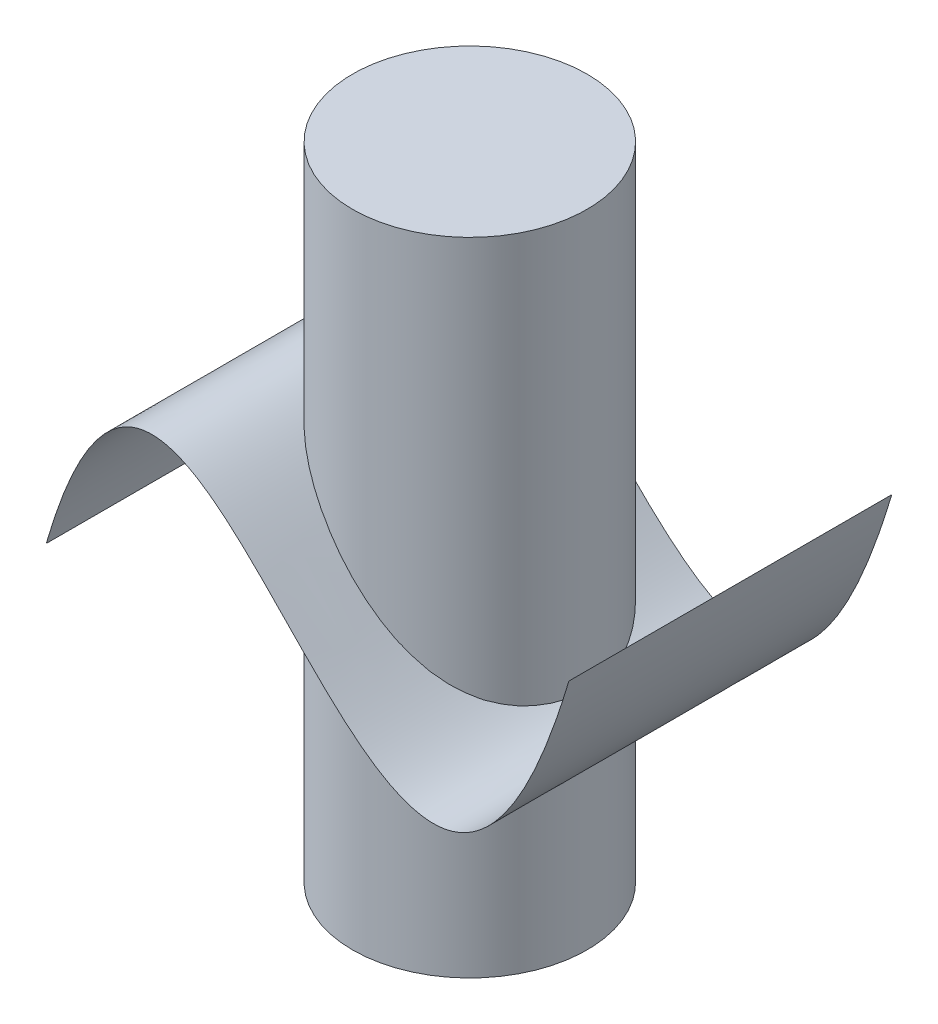
SolidWorks part; units mm, degrees
ref_plane "前视基准面" through (0, 0, 0) normal (0, 0, 1) x (1, 0, 0)
ref_plane "上视基准面" through (0, 0, 0) normal (0, 1, 0) x (1, 0, 0)
ref_plane "右视基准面" through (0, 0, 0) normal (1, 0, 0) x (0, 0, -1)
other "Configuration Table"
sketch "草图1" plane through (0, 0, 0) normal (0, 0, 1) x (1, 0, 0)
  spline S0 degree 3 poles (-85.8726, -24.0496) (-22.8274, 193.3741) (74.8967, -213.2331) (150.4405, 40.2569) knots 0 0 0 0 1 1 1 1
surface "曲面-拉伸1" sketch "草图1" parameters "D1"=146
sketch "草图2" plane through (0, 0, 0) normal (0, 1, 0) x (1, 0, 0)
  circle A0 centre (21.5976, 11.0548) radius 53.0044
  point P2 (21.1063, 28.4968)
  point P3 (21.5976, 11.0548)
extrude "凸台-拉伸1" add sketch "草图2" along normal mid plane 290
sketch3d "3D草图1"
  spline S0 degree 3 poles (21.2444, 1.1157, -64.0592) (24.4232, -2.1595, -64.0592) (27.2203, -5.0469, -63.8359) (32.8022, -10.7278, -62.9385) (35.5868, -13.5217, -62.2648) (39.7817, -17.6026, -60.8643) (41.1829, -18.9445, -60.3319) (43.2923, -20.9235, -59.4221) (43.9967, -21.5776, -59.1003) (45.4084, -22.8733, -58.4165) (46.1141, -23.5134, -58.0553) (49.6189, -26.6515, -56.1596) (52.3702, -28.9826, -54.3496) (55.7189, -31.6232, -51.6252) (56.384, -32.1376, -51.0569) (57.7034, -33.1377, -49.8701) (58.3577, -33.6233, -49.2514) (60.2754, -35.016, -47.3419) (61.5027, -35.8662, -45.9902) (63.8424, -37.4146, -43.1215) (64.9549, -38.1127, -41.6045) (66.524, -39.0507, -39.1974) (67.0304, -39.3452, -38.3731) (68.0071, -39.8989, -36.6788) (68.4789, -40.1588, -35.8054) (69.8161, -40.8772, -33.1539) (70.6083, -41.2774, -31.3373) (71.9898, -41.9474, -27.6093) (72.5791, -42.2173, -25.698) (73.3033, -42.5391, -22.7599) (73.5183, -42.6327, -21.7668) (73.8915, -42.7928, -19.7643) (74.0485, -42.859, -18.7616) (74.4325, -43.0195, -15.7495) (74.5727, -43.0762, -13.7358) (74.6231, -43.0968, -9.6977) (74.5334, -43.0607, -7.6732) (74.2209, -42.9311, -4.6279) (74.0874, -42.8755, -3.6174) (73.7652, -42.7389, -1.6188) (73.5762, -42.6579, -0.6286) (72.9276, -42.3742, 2.3146) (72.3865, -42.1312, 4.2407) (71.4152, -41.6698, 7.0745) (71.0649, -41.4998, 8.0099) (70.3108, -41.1238, 9.8617) (69.9055, -40.9168, 10.7812) (67.775, -39.7977, 15.2683) (65.7316, -38.6277, 18.5404) (62.8356, -36.7512, 22.2586) (62.2378, -36.3543, 22.9851) (61.0149, -35.5218, 24.394) (60.3932, -35.0885, 25.0727) (58.5007, -33.7385, 27.0364) (57.2027, -32.7716, 28.2489) (54.5469, -30.7104, 30.5005) (53.1891, -29.6161, 31.5396) (50.4217, -27.3072, 33.459) (49.0329, -26.11, 34.325) (44.8579, -22.4107, 36.6803) (42.0622, -19.8002, 37.9306) (37.8426, -15.7226, 39.4209) (36.4315, -14.3362, 39.8527) (33.5971, -11.5166, 40.5943) (32.1853, -10.095, 40.901) (27.9697, -5.8163, 41.6425) (25.18, -2.94, 41.9021) (19.5961, 2.8146, 41.9854) (16.8022, 5.6932, 41.8091) (12.5721, 9.9776, 41.195) (11.1542, 11.4013, 40.9312) (8.3031, 14.2255, 40.2761) (6.8812, 15.615, 39.8875) (2.6197, 19.7021, 38.5255) (-0.2161, 22.3198, 37.3596) (-3.7705, 25.4021, 35.4917) (-4.4818, 26.009, 35.0973) (-5.9056, 27.2019, 34.2633) (-6.6175, 27.7873, 33.8238) (-8.7325, 29.4919, 32.4467) (-10.1221, 30.5651, 31.4468) (-12.8536, 32.5745, 29.2644) (-14.1954, 33.5105, 28.0822) (-16.1629, 34.8043, 26.1535) (-16.8127, 35.2181, 25.483) (-18.0876, 36.0035, 24.094) (-18.7087, 36.3727, 23.3803) (-21.7284, 38.1056, 19.7147) (-23.8739, 39.1283, 16.4734) (-26.1334, 40.0572, 12.015) (-26.5651, 40.226, 11.1001) (-27.3717, 40.5281, 9.2551) (-27.748, 40.662, 8.3227) (-28.7965, 41.02, 5.4963) (-29.3883, 41.2006, 3.5733) (-30.1122, 41.4086, 0.6323) (-30.3261, 41.4674, -0.3575) (-30.698, 41.5668, -2.356) (-30.8562, 41.6074, -3.3672) (-31.2406, 41.7043, -6.3938) (-31.3793, 41.7368, -8.4115) (-31.4269, 41.7482, -12.4467) (-31.3359, 41.7271, -14.4643) (-31.0244, 41.65, -17.4905) (-30.8911, 41.6165, -18.5006) (-30.5657, 41.5318, -20.5149) (-30.3749, 41.4809, -21.5119) (-29.7203, 41.2986, -24.4723) (-29.1747, 41.1381, -26.4056) (-27.8726, 40.7101, -30.1905) (-27.116, 40.4426, -32.0422) (-25.8234, 39.9321, -34.7554) (-25.3642, 39.7427, -35.6526) (-24.4054, 39.3274, -37.4023) (-23.9058, 39.1016, -38.2553) (-22.3507, 38.3659, -40.7509) (-21.2391, 37.7974, -42.3296) (-18.8838, 36.4874, -45.3236) (-17.6402, 35.7458, -46.7388) (-15.6851, 34.4942, -48.7422) (-15.0237, 34.0573, -49.3846) (-13.6891, 33.1484, -50.6167) (-13.0149, 32.676, -51.2073) (-10.9744, 31.2067, -52.9078) (-9.5899, 30.1578, -53.9464) (-7.4834, 28.4889, -55.3773) (-6.7762, 27.9167, -55.8331) (-5.3522, 26.7418, -56.7042) (-4.64, 26.1428, -57.1169) (-2.5069, 24.3179, -58.289) (-1.0876, 23.0623, -58.9844) (1.748, 20.4862, -60.2265) (3.1644, 19.1655, -60.7732) (5.9979, 16.4697, -61.7337) (7.415, 15.0944, -62.1475) (10.2544, 12.2982, -62.8519) (11.6798, 10.8741, -63.143) (14.5206, 8.0078, -63.6044) (15.9369, 6.565, -63.7752) (18.0598, 4.3912, -63.9458) (18.7671, 3.6649, -63.9883) (19.8283, 2.5738, -64.0309) (20.182, 2.2097, -64.0415) (20.8897, 1.4811, -64.0557) (21.2444, 1.1157, -64.0592) (24.4232, -2.1595, -64.0592) (27.2203, -5.0469, -63.8359) knots -0.003906 -0.003906 0 0 0.03125 0.03125 0.0625 0.0625 0.078125 0.078125 0.085938 0.085938 0.09375 0.09375 0.125 0.125 0.132813 0.132813 0.140625 0.140625 0.15625 0.15625 0.171875 0.171875 0.179688 0.179688 0.1875 0.1875 0.203125 0.203125 0.21875 0.21875 0.226563 0.226563 0.234375 0.234375 0.25 0.25 0.265625 0.265625 0.273438 0.273438 0.28125 0.28125 0.296875 0.296875 0.304688 0.304688 0.3125 0.3125 0.34375 0.34375 0.351563 0.351563 0.359375 0.359375 0.375 0.375 0.390625 0.390625 0.40625 0.40625 0.4375 0.4375 0.453125 0.453125 0.46875 0.46875 0.5 0.5 0.53125 0.53125 0.546875 0.546875 0.5625 0.5625 0.59375 0.59375 0.601563 0.601563 0.609375 0.609375 0.625 0.625 0.640625 0.640625 0.648438 0.648438 0.65625 0.65625 0.6875 0.6875 0.695313 0.695313 0.703125 0.703125 0.71875 0.71875 0.726563 0.726563 0.734375 0.734375 0.75 0.75 0.765625 0.765625 0.773438 0.773438 0.78125 0.78125 0.796875 0.796875 0.8125 0.8125 0.820313 0.820313 0.828125 0.828125 0.84375 0.84375 0.859375 0.859375 0.867188 0.867188 0.875 0.875 0.890625 0.890625 0.898438 0.898438 0.90625 0.90625 0.921875 0.921875 0.9375 0.9375 0.953125 0.953125 0.96875 0.96875 0.984375 0.984375 0.992188 0.992188 0.996094 0.996094 1 1 1.03125 1.03125 1.0625 only from (21.5976, 0.7518, -64.0592) to (21.5976, 0.7518, -64.0592)
  spline S1 degree 3 poles (21.2444, 1.1157, -64.0592) (24.4232, -2.1595, -64.0592) (27.2203, -5.0469, -63.8359) (32.8022, -10.7278, -62.9385) (35.5868, -13.5217, -62.2648) (39.7817, -17.6026, -60.8643) (41.1829, -18.9445, -60.3319) (43.2923, -20.9235, -59.4221) (43.9967, -21.5776, -59.1003) (45.4084, -22.8733, -58.4165) (46.1141, -23.5134, -58.0553) (49.6189, -26.6515, -56.1596) (52.3702, -28.9826, -54.3496) (55.7189, -31.6232, -51.6252) (56.384, -32.1376, -51.0569) (57.7034, -33.1377, -49.8701) (58.3577, -33.6233, -49.2514) (60.2754, -35.016, -47.3419) (61.5027, -35.8662, -45.9902) (63.8424, -37.4146, -43.1215) (64.9549, -38.1127, -41.6045) (66.524, -39.0507, -39.1974) (67.0304, -39.3452, -38.3731) (68.0071, -39.8989, -36.6788) (68.4789, -40.1588, -35.8054) (69.8161, -40.8772, -33.1539) (70.6083, -41.2774, -31.3373) (71.9898, -41.9474, -27.6093) (72.5791, -42.2173, -25.698) (73.3033, -42.5391, -22.7599) (73.5183, -42.6327, -21.7668) (73.8915, -42.7928, -19.7643) (74.0485, -42.859, -18.7616) (74.4325, -43.0195, -15.7495) (74.5727, -43.0762, -13.7358) (74.6231, -43.0968, -9.6977) (74.5334, -43.0607, -7.6732) (74.2209, -42.9311, -4.6279) (74.0874, -42.8755, -3.6174) (73.7652, -42.7389, -1.6188) (73.5762, -42.6579, -0.6286) (72.9276, -42.3742, 2.3146) (72.3865, -42.1312, 4.2407) (71.4152, -41.6698, 7.0745) (71.0649, -41.4998, 8.0099) (70.3108, -41.1238, 9.8617) (69.9055, -40.9168, 10.7812) (67.775, -39.7977, 15.2683) (65.7316, -38.6277, 18.5404) (62.8356, -36.7512, 22.2586) (62.2378, -36.3543, 22.9851) (61.0149, -35.5218, 24.394) (60.3932, -35.0885, 25.0727) (58.5007, -33.7385, 27.0364) (57.2027, -32.7716, 28.2489) (54.5469, -30.7104, 30.5005) (53.1891, -29.6161, 31.5396) (50.4217, -27.3072, 33.459) (49.0329, -26.11, 34.325) (44.8579, -22.4107, 36.6803) (42.0622, -19.8002, 37.9306) (37.8426, -15.7226, 39.4209) (36.4315, -14.3362, 39.8527) (33.5971, -11.5166, 40.5943) (32.1853, -10.095, 40.901) (27.9697, -5.8163, 41.6425) (25.18, -2.94, 41.9021) (19.5961, 2.8146, 41.9854) (16.8022, 5.6932, 41.8091) (12.5721, 9.9776, 41.195) (11.1542, 11.4013, 40.9312) (8.3031, 14.2255, 40.2761) (6.8812, 15.615, 39.8875) (2.6197, 19.7021, 38.5255) (-0.2161, 22.3198, 37.3596) (-3.7705, 25.4021, 35.4917) (-4.4818, 26.009, 35.0973) (-5.9056, 27.2019, 34.2633) (-6.6175, 27.7873, 33.8238) (-8.7325, 29.4919, 32.4467) (-10.1221, 30.5651, 31.4468) (-12.8536, 32.5745, 29.2644) (-14.1954, 33.5105, 28.0822) (-16.1629, 34.8043, 26.1535) (-16.8127, 35.2181, 25.483) (-18.0876, 36.0035, 24.094) (-18.7087, 36.3727, 23.3803) (-21.7284, 38.1056, 19.7147) (-23.8739, 39.1283, 16.4734) (-26.1334, 40.0572, 12.015) (-26.5651, 40.226, 11.1001) (-27.3717, 40.5281, 9.2551) (-27.748, 40.662, 8.3227) (-28.7965, 41.02, 5.4963) (-29.3883, 41.2006, 3.5733) (-30.1122, 41.4086, 0.6323) (-30.3261, 41.4674, -0.3575) (-30.698, 41.5668, -2.356) (-30.8562, 41.6074, -3.3672) (-31.2406, 41.7043, -6.3938) (-31.3793, 41.7368, -8.4115) (-31.4269, 41.7482, -12.4467) (-31.3359, 41.7271, -14.4643) (-31.0244, 41.65, -17.4905) (-30.8911, 41.6165, -18.5006) (-30.5657, 41.5318, -20.5149) (-30.3749, 41.4809, -21.5119) (-29.7203, 41.2986, -24.4723) (-29.1747, 41.1381, -26.4056) (-27.8726, 40.7101, -30.1905) (-27.116, 40.4426, -32.0422) (-25.8234, 39.9321, -34.7554) (-25.3642, 39.7427, -35.6526) (-24.4054, 39.3274, -37.4023) (-23.9058, 39.1016, -38.2553) (-22.3507, 38.3659, -40.7509) (-21.2391, 37.7974, -42.3296) (-18.8838, 36.4874, -45.3236) (-17.6402, 35.7458, -46.7388) (-15.6851, 34.4942, -48.7422) (-15.0237, 34.0573, -49.3846) (-13.6891, 33.1484, -50.6167) (-13.0149, 32.676, -51.2073) (-10.9744, 31.2067, -52.9078) (-9.5899, 30.1578, -53.9464) (-7.4834, 28.4889, -55.3773) (-6.7762, 27.9167, -55.8331) (-5.3522, 26.7418, -56.7042) (-4.64, 26.1428, -57.1169) (-2.5069, 24.3179, -58.289) (-1.0876, 23.0623, -58.9844) (1.748, 20.4862, -60.2265) (3.1644, 19.1655, -60.7732) (5.9979, 16.4697, -61.7337) (7.415, 15.0944, -62.1475) (10.2544, 12.2982, -62.8519) (11.6798, 10.8741, -63.143) (14.5206, 8.0078, -63.6044) (15.9369, 6.565, -63.7752) (18.0598, 4.3912, -63.9458) (18.7671, 3.6649, -63.9883) (19.8283, 2.5738, -64.0309) (20.182, 2.2097, -64.0415) (20.8897, 1.4811, -64.0557) (21.2444, 1.1157, -64.0592) (24.4232, -2.1595, -64.0592) (27.2203, -5.0469, -63.8359) knots -0.003906 -0.003906 0 0 0.03125 0.03125 0.0625 0.0625 0.078125 0.078125 0.085938 0.085938 0.09375 0.09375 0.125 0.125 0.132813 0.132813 0.140625 0.140625 0.15625 0.15625 0.171875 0.171875 0.179688 0.179688 0.1875 0.1875 0.203125 0.203125 0.21875 0.21875 0.226563 0.226563 0.234375 0.234375 0.25 0.25 0.265625 0.265625 0.273438 0.273438 0.28125 0.28125 0.296875 0.296875 0.304688 0.304688 0.3125 0.3125 0.34375 0.34375 0.351563 0.351563 0.359375 0.359375 0.375 0.375 0.390625 0.390625 0.40625 0.40625 0.4375 0.4375 0.453125 0.453125 0.46875 0.46875 0.5 0.5 0.53125 0.53125 0.546875 0.546875 0.5625 0.5625 0.59375 0.59375 0.601563 0.601563 0.609375 0.609375 0.625 0.625 0.640625 0.640625 0.648438 0.648438 0.65625 0.65625 0.6875 0.6875 0.695313 0.695313 0.703125 0.703125 0.71875 0.71875 0.726563 0.726563 0.734375 0.734375 0.75 0.75 0.765625 0.765625 0.773438 0.773438 0.78125 0.78125 0.796875 0.796875 0.8125 0.8125 0.820313 0.820313 0.828125 0.828125 0.84375 0.84375 0.859375 0.859375 0.867188 0.867188 0.875 0.875 0.890625 0.890625 0.898438 0.898438 0.90625 0.90625 0.921875 0.921875 0.9375 0.9375 0.953125 0.953125 0.96875 0.96875 0.984375 0.984375 0.992188 0.992188 0.996094 0.996094 1 1 1.03125 1.03125 1.0625 only from (21.5976, 0.7518, -64.0592) to (21.5976, 0.7518, -64.0592)
